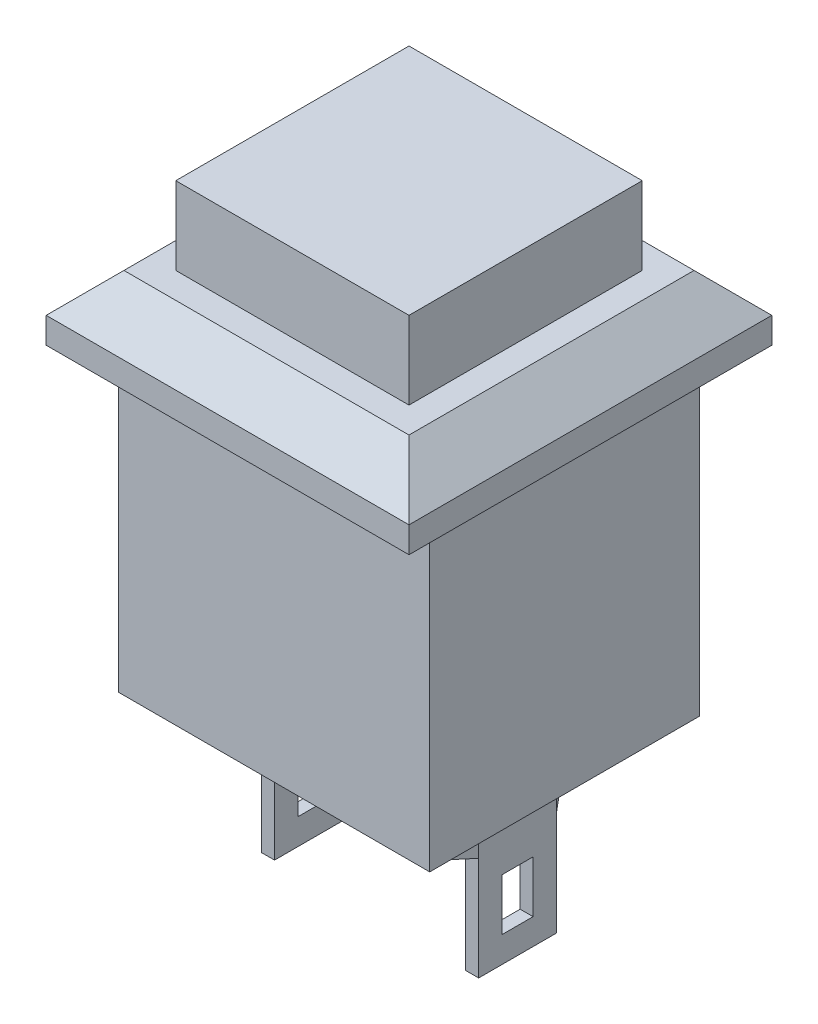
SolidWorks part; units mm, degrees
ref_plane "Спереди" through (0, 0, 0) normal (0, 0, 1) x (1, 0, 0)
ref_plane "Сверху" through (0, 0, 0) normal (0, 1, 0) x (1, 0, 0)
ref_plane "Справа" through (0, 0, 0) normal (1, 0, 0) x (0, 0, -1)
sketch "Эскиз1" plane through (0, 0, 0) normal (0, 1, 0) x (1, 0, 0)
  line L1 (-4.5, -4.5) -> (4.5, -4.5)
  line L2 (-4.5, -4.5) -> (-4.5, 4.5)
  line L3 (-4.5, 4.5) -> (4.5, 4.5)
  line L4 (4.5, -4.5) -> (4.5, 4.5)
  line L5 (-4.5, -4.5) -> (4.5, 4.5) construction
  line L6 (-4.5, 4.5) -> (4.5, -4.5) construction
  point P0 (0, 0)
  dimension "D1" = 9
extrude "Бобышка-Вытянуть1" add sketch "Эскиз1" along normal blind 3
sketch "Эскиз2" plane through (0, 0, 0) normal (0, -1, 0) x (1, 0, 0)
  line L1 (-7, 7) -> (7, 7)
  line L2 (-7, 7) -> (-7, -7)
  line L3 (-7, -7) -> (7, -7)
  line L4 (7, 7) -> (7, -7)
  line L5 (-7, 7) -> (7, -7) construction
  line L6 (-7, -7) -> (7, 7) construction
  point P0 (0, 0)
  dimension "D1" = 14
extrude "Бобышка-Вытянуть2" add sketch "Эскиз2" along normal blind 2.5
chamfer "Фаска1" distance 1.5 angle 45 4 edges at (0, 0, -7) (-7, 0, 0) (0, 0, 7) (7, 0, 0)
sketch "Эскиз3" plane through (0, -2.5, 0) normal (0, -1, 0) x (1, 0, 0)
  line L1 (-6, 5.2) -> (6, 5.2)
  line L2 (-6, 5.2) -> (-6, -5.2)
  line L3 (-6, -5.2) -> (6, -5.2)
  line L4 (6, 5.2) -> (6, -5.2)
  line L5 (-6, 5.2) -> (6, -5.2) construction
  line L6 (-6, -5.2) -> (6, 5.2) construction
  point P0 (0, 0)
  dimension "D1" = 10.4
  dimension "D2" = 12
extrude "Бобышка-Вытянуть3" add sketch "Эскиз3" along normal blind 12
sketch "Эскиз4" plane through (0, -14.5, 0) normal (0, -1, 0) x (1, 0, 0)
  line L0 (0, 0) -> (4.1887, 0) construction
  line L5 (4.1887, -1.5) -> (4.1887, 1.5)
  line L6 (4.1887, 1.5) -> (3.3423, 2.5)
  line L7 (3.3423, 2.5) -> (2.9607, 2.177)
  line L8 (2.9607, 2.177) -> (3.6887, 1.3168)
  line L9 (3.6887, 1.3168) -> (3.6887, -1.3168)
  line L10 (2.9607, -2.177) -> (3.6887, -1.3168)
  line L11 (3.3423, -2.5) -> (2.9607, -2.177)
  line L12 (4.1887, -1.5) -> (3.3423, -2.5)
  point P9 (3.6887, 0)
  dimension "D1" = 0.5
  dimension "D2" = 0.5
  dimension "D3" = 1.5
  dimension "D4" = 2.5
extrude "Бобышка-Вытянуть4" add sketch "Эскиз4" along normal blind 2.3
sketch "Эскиз5" plane through (0, -16.8, 0) normal (0, -1, 0) x (1, 0, 0)
  line L0 (4.1887, -1.5) -> (4.1887, 1.5) construction
  line L1 (4.1887, 1.5) -> (3.6887, 1.5)
  line L2 (4.1887, 1.5) -> (4.1887, -1.5)
  line L3 (4.1887, -1.5) -> (3.6887, -1.5)
  line L4 (3.6887, 1.5) -> (3.6887, -1.5)
  line L5 (3.6887, 1.3168) -> (3.6887, -1.3168) construction
  point P8 (3.6887, 0)
  dimension "D1" = 3
extrude "Бобышка-Вытянуть5" add sketch "Эскиз5" along normal blind 4
sketch "Эскиз6" plane through (3.6887, 0, 0) normal (-1, 0, 0) x (0, 0, 1)
  line L0 (1.5, -20.8) -> (-1.5, -20.8) construction
  line L1 (0.6, -17.8) -> (-0.6, -17.8)
  line L2 (0.6, -17.8) -> (0.6, -19.8)
  line L3 (0.6, -19.8) -> (-0.6, -19.8)
  line L4 (-0.6, -17.8) -> (-0.6, -19.8)
  line L5 (0.6, -17.8) -> (-0.6, -19.8) construction
  line L6 (0.6, -19.8) -> (-0.6, -17.8) construction
  point P0 (0, -18.8)
  point P7 (0, 0)
  dimension "D1" = 1.2
  dimension "D2" = 2
  dimension "D3" = 1
extrude "Вырез-Вытянуть1" cut sketch "Эскиз6" against normal blind 4
mirror "Зеркальное отражение1" about plane through (0, 0, 0) normal (1, 0, 0) of "Вырез-Вытянуть1", "Бобышка-Вытянуть5", "Бобышка-Вытянуть4"
